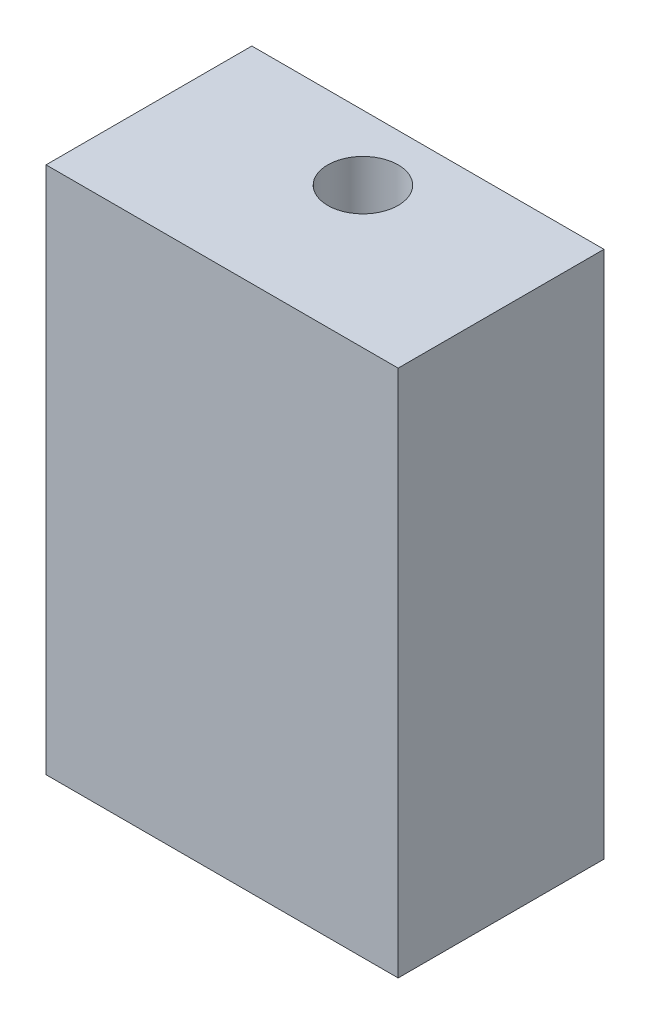
SolidWorks part; units mm, degrees
ref_plane "Спереди" through (0, 0, 0) normal (0, 0, 1) x (1, 0, 0)
ref_plane "Сверху" through (0, 0, 0) normal (0, 1, 0) x (1, 0, 0)
ref_plane "Справа" through (0, 0, 0) normal (1, 0, 0) x (0, 0, -1)
other "Configuration Table"
sketch "Эскиз1" plane through (0, 0, 0) normal (0, 1, 0) x (1, 0, 0)
  line L5 (-10, 3.69) -> (10, 3.69)
  line L6 (-10, 3.69) -> (-10, -8)
  line L7 (-10, -8) -> (10, -8)
  line L8 (10, 3.69) -> (10, -8)
  circle A0 centre (0, 0) radius 2
  dimension "D1" = 3.69
  dimension "D2" = 8
  dimension "D3" = 10
  dimension "D4" = 10
extrude "Бобышка-Вытянуть1" add sketch "Эскиз1" along normal blind 30
